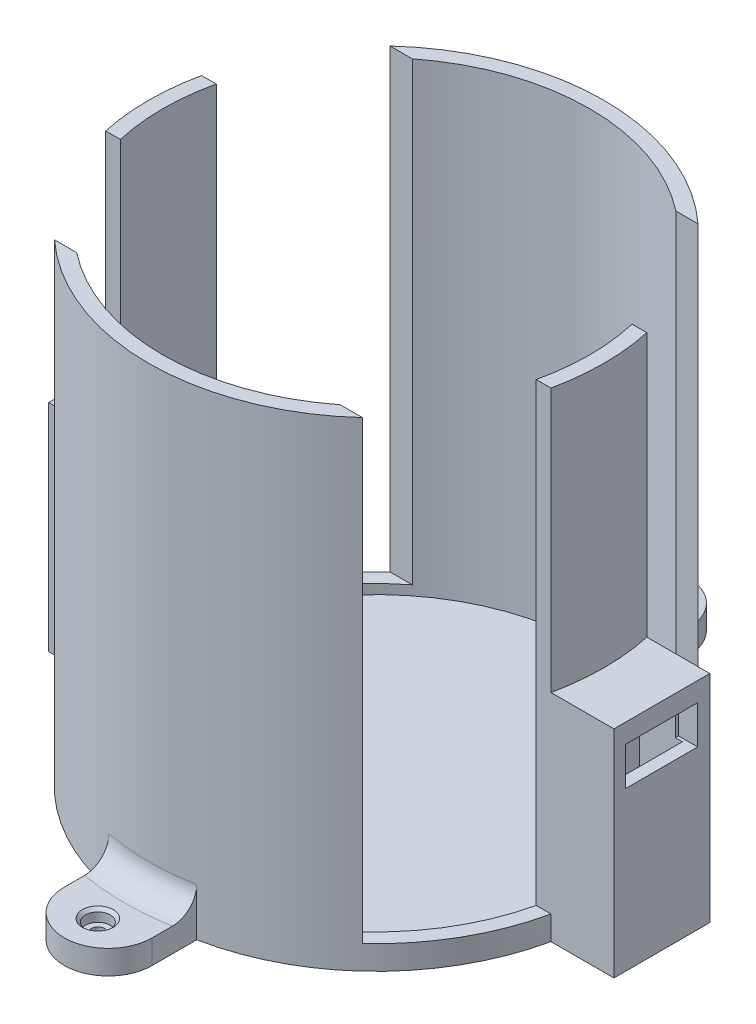
SolidWorks part; units mm, degrees
ref_plane "Front Plane" through (0, 0, 0) normal (0, 0, 1) x (1, 0, 0)
ref_plane "Top Plane" through (0, 0, 0) normal (0, 1, 0) x (1, 0, 0)
ref_plane "Right Plane" through (0, 0, 0) normal (1, 0, 0) x (0, 0, -1)
sketch "Sketch2" plane through (0, 0, 0) normal (0, 1, 0) x (1, 0, 0)
  circle A0 centre (0, 0) radius 47.5
  dimension "D1" = 95
extrude "Boss-Extrude2" add sketch "Sketch2" along normal blind 100
sketch "Sketch3" plane through (0, 100, 0) normal (0, 1, 0) x (1, 0, 0)
  circle A0 centre (0, 0) radius 44.5
  dimension "D1" = 89
extrude "Cut-Extrude1" cut sketch "Sketch3" against normal blind 97 contours A0
sketch "Sketch4" plane through (0, 100, 0) normal (0, 1, 0) x (1, 0, 0)
  line L17 (-70.3949, -10) -> (75.1778, -10)
  line L18 (-70.3949, 35) -> (88.7009, 35)
  line L19 (-70.3949, 35) -> (-70.3949, 10)
  line L20 (-70.3949, 10) -> (88.7009, 10)
  line L21 (88.7009, 35) -> (88.7009, 10)
  line L22 (-70.3949, -10) -> (-70.3949, -35)
  line L23 (-70.3949, -35) -> (75.1778, -35)
  line L24 (75.1778, -10) -> (75.1778, -35)
  circle A0 centre (0, 0) radius 44.5 construction
  point P0 (0, 0)
  dimension "D3" = 35
  dimension "D1" = 25
  dimension "D2" = 25
  dimension "D4" = 35
extrude "Cut-Extrude3" cut sketch "Sketch4" against normal blind 95
sketch "Sketch5" plane through (0, 0, 0) normal (0, -1, 0) x (1, 0, 0)
  line L1 (-9.1623, 46.608) -> (-9.1623, 55.9035)
  line L2 (9.1623, 46.608) -> (9.1623, 55.9035)
  line L4 (9.1623, -46.608) -> (9.1623, -55.9035)
  line L5 (-9.1623, -46.608) -> (-9.1623, -55.9035)
  arc A11 (9.1623, 55.9035) -> (-9.1623, 55.9035) centre (0, 55.9035) ccw
  arc A13 (-9.1623, -55.9035) -> (9.1623, -55.9035) centre (0, -55.9035) ccw
  arc A14 (9.1623, 46.608) -> (-9.1623, 46.608) centre (0, 0) ccw
  arc A15 (-9.1623, -46.608) -> (9.1623, -46.608) centre (0, 0) ccw
  point P2 (0, 50)
  point P7 (0, -50)
  dimension "D1" = 50
  dimension "D3" = 95
  dimension "D2" = 50
extrude "Boss-Extrude3" add sketch "Sketch5" against normal blind 5
fillet "Fillet1" radius 5 2 edges at (0, 5, -47.5) (0, 5, 47.5)
hole_wizard "CBORE for #3 Socket Head Cap Screw1" positions "Sketch6" profile "Sketch8" counterbore size "#3" standard "ANSI Inch" end condition through all
sketch "Sketch6" plane through (0, 5, 0) normal (0, 1, 0) x (1, 0, 0)
  arc A0 (-9.1623, -55.9035) -> (9.1623, -55.9035) centre (0, -55.9035) ccw construction
  arc A1 (9.1623, 55.9035) -> (-9.1623, 55.9035) centre (0, 55.9035) ccw construction
  point P0 (0, -58.0657)
  point P2 (0, 58.0657)
  point P8 (0, -65.0657)
  point P12 (0, 65.0657)
  dimension "D1" = 7
  dimension "D2" = 7
sketch "Sketch8" plane through (0, 5, 58.0657) normal (1, 0, 0) x (0, 0, 1)
  line L0 (0, 0) -> (0, 5)
  line L1 (0, 5) -> (1.397, 5)
  line L3 (1.397, 5) -> (1.397, 2.5146)
  line L4 (2.5794, 2.5146) -> (1.397, 2.5146)
  line L5 (2.5794, 2.5146) -> (2.5794, 0.635)
  line L6 (2.5794, 0.635) -> (3.2144, 0)
  line L7 (3.2144, 0) -> (0, 0)
  line L8 (-2.5794, 0.635) -> (-3.2144, 0) construction
  line L11 (0, -6.35) -> (0, 107.95) construction
  dimension "Thru Hole Dia." = 2.794
  dimension "Thru Hole Depth" = 5
  dimension "C'Bore Dia." = 5.1587
  dimension "C'Bore Depth" = 2.5146
  dimension "Near C'Sink Dia." = 6.4287
  dimension "Near C'Sink Angle" = 90
sketch "Sketch9" plane through (0, 0, 0) normal (0, -1, 0) x (1, 0, 0)
  line L1 (-58.3256, 10) -> (-46.4354, 10)
  line L2 (-58.3256, 10) -> (-58.3256, -10)
  line L3 (-58.3256, -10) -> (-46.4354, -10)
  line L5 (46.4354, 10) -> (59.5666, 10)
  line L7 (46.4354, -10) -> (59.5666, -10)
  line L8 (59.5666, 10) -> (59.5666, -10)
  arc A1 (-46.4354, 10) -> (-46.4354, -10) centre (0, 0) ccw
  arc A2 (46.4354, -10) -> (46.4354, 10) centre (0, 0) ccw
  dimension "D1" = 20
  dimension "D2" = 20
extrude "Boss-Extrude4" add sketch "Sketch9" against normal blind 45
sketch "Sketch10" plane through (0, 0, 0) normal (0, -1, 0) x (1, 0, 0)
  line L1 (-56.1022, 7.1893) -> (-47.1022, 7.1893)
  line L2 (-56.1022, 7.1893) -> (-56.1022, -6.8107)
  line L3 (-56.1022, -6.8107) -> (-47.1022, -6.8107)
  line L4 (-47.1022, 7.1893) -> (-47.1022, -6.8107)
  line L5 (57.046, 7.1893) -> (48.046, 7.1893)
  line L6 (57.046, 7.1893) -> (57.046, -6.8107)
  line L7 (57.046, -6.8107) -> (48.046, -6.8107)
  line L8 (48.046, 7.1893) -> (48.046, -6.8107)
  dimension "D1" = 14
  dimension "D2" = 14
  dimension "D3" = 9
  dimension "D4" = 9
extrude "Cut-Extrude4" cut sketch "Sketch10" against normal blind 43 contours L3 L4 L1 L2 | L6 L5 L8 L7
sketch "Sketch11" plane through (59.5666, 0, 0) normal (1, 0, 0) x (0, 0, -1)
  line L0 (10, 45) -> (-10, 45) construction
  line L1 (-7.5345, 41) -> (7.4655, 41)
  line L2 (-7.5345, 41) -> (-7.5345, 33)
  line L3 (-7.5345, 33) -> (7.4655, 33)
  line L4 (7.4655, 41) -> (7.4655, 33)
  dimension "D1" = 8
  dimension "D2" = 15
  dimension "D3" = 4
extrude "Cut-Extrude5" cut sketch "Sketch11" against normal blind 4
sketch "Sketch12" plane through (-58.3256, 0, 0) normal (-1, 0, 0) x (0, 0, 1)
  line L0 (10, 45) -> (-10, 45) construction
  line L1 (-7.1235, 41) -> (7.8765, 41)
  line L2 (-7.1235, 41) -> (-7.1235, 33)
  line L3 (-7.1235, 33) -> (7.8765, 33)
  line L4 (7.8765, 41) -> (7.8765, 33)
  point P4 (0.3765, 41)
  point P7 (0, 45)
  dimension "D1" = 8
  dimension "D2" = 15
  dimension "D3" = 4
extrude "Cut-Extrude6" cut sketch "Sketch12" against normal blind 4
sketch "Sketch13" plane through (-58.3256, 0, 0) normal (-1, 0, 0) x (0, 0, 1)
  line L0 (10, 45) -> (-10, 45) construction
  circle A0 centre (0, 36.5) radius 3.15
  point P4 (0, 45)
  point P5 (0, 0)
  dimension "D1" = 6.3
  dimension "D2" = 8.5
extrude "Cut-Extrude7" cut sketch "Sketch13" against normal up to next
sketch "Sketch14" plane through (48.046, 0, 0) normal (1, 0, 0) x (0, 0, -1)
  line L0 (10, 45) -> (-10, 45) construction
  circle A0 centre (0, 36.5) radius 2.65
  point P4 (0, 45)
  point P5 (0, 0)
  dimension "D2" = 5.3
  dimension "D1" = 8.5
extrude "Cut-Extrude8" cut sketch "Sketch14" against normal up to next
